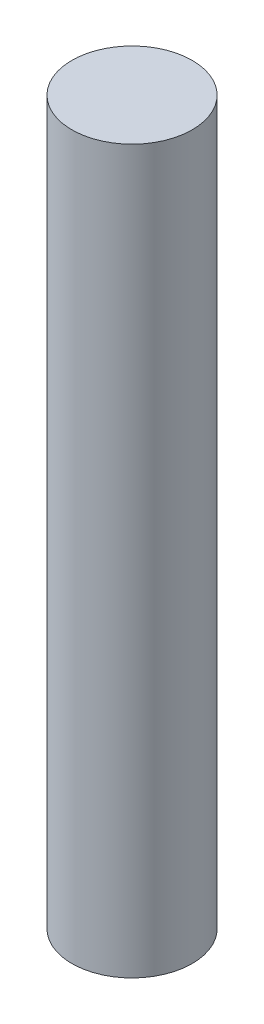
SolidWorks part; units mm, degrees
ref_plane "Front Plane" through (0, 0, 0) normal (0, 0, 1) x (1, 0, 0)
ref_plane "Top Plane" through (0, 0, 0) normal (0, 1, 0) x (1, 0, 0)
ref_plane "Right Plane" through (0, 0, 0) normal (1, 0, 0) x (0, 0, -1)
sketch "Sketch1" plane through (0, 0, 0) normal (0, 1, 0) x (1, 0, 0)
  circle A0 centre (0, 0) radius 12.7
  point P3 (0, 0)
  dimension "D1" = 25.4
extrude "Boss-Extrude1" add sketch "Sketch1" along normal blind 152.4
